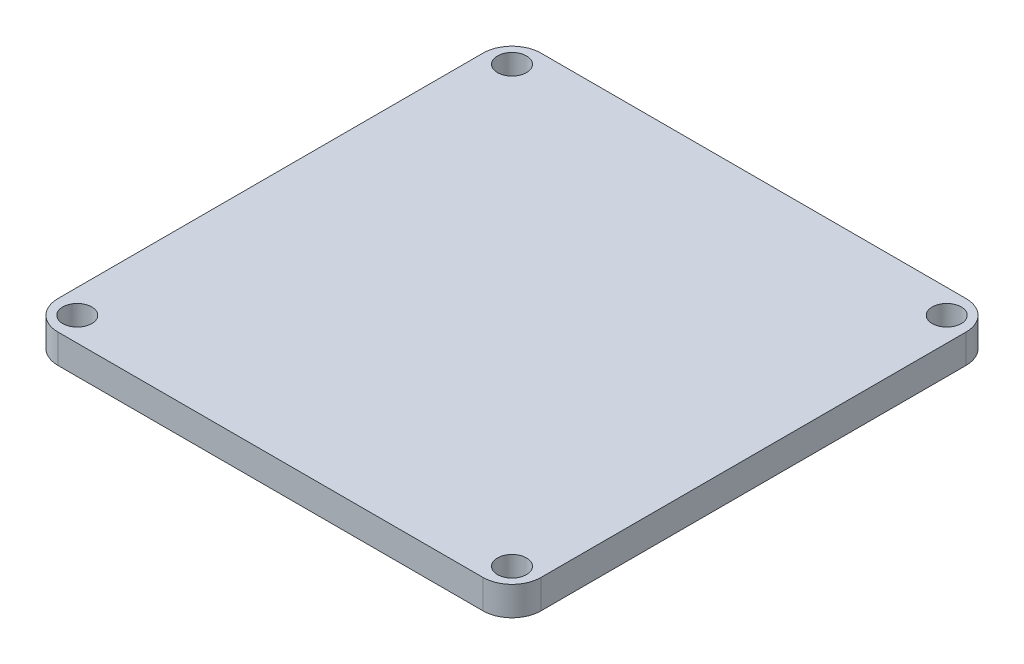
SolidWorks part; units mm, degrees
ref_plane "前基準面" through (0, 0, 0) normal (0, 0, 1) x (1, 0, 0)
ref_plane "上基準面" through (0, 0, 0) normal (0, 1, 0) x (1, 0, 0)
ref_plane "右基準面" through (0, 0, 0) normal (1, 0, 0) x (0, 0, -1)
sketch "草圖1" plane through (0, 0, 0) normal (0, 1, 0) x (1, 0, 0)
  line L1 (-22, 25) -> (22, 25)
  line L2 (-25, 22) -> (-25, -22)
  line L3 (-22, -25) -> (22, -25)
  line L4 (25, 22) -> (25, -22)
  line L5 (-25, 25) -> (25, -25) construction
  line L6 (-25, -25) -> (25, 25) construction
  line L7 (-22.5, -22.5) -> (22.5, -22.5) construction
  line L8 (-22.5, -22.5) -> (-22.5, 22.5) construction
  line L9 (-22.5, 22.5) -> (22.5, 22.5) construction
  line L10 (22.5, -22.5) -> (22.5, 22.5) construction
  line L11 (-22.5, -22.5) -> (22.5, 22.5) construction
  line L12 (-22.5, 22.5) -> (22.5, -22.5) construction
  arc A0 (-25, -22) -> (-22, -25) centre (-22, -22) ccw
  arc A1 (22, -25) -> (25, -22) centre (22, -22) ccw
  arc A2 (22, 25) -> (25, 22) centre (22, 22) cw
  arc A3 (-22, 25) -> (-25, 22) centre (-22, 22) ccw
  circle A4 centre (-22.5, 22.5) radius 1.5
  circle A5 centre (22.5, 22.5) radius 1.5
  circle A6 centre (-22.5, -22.5) radius 1.5
  circle A7 centre (22.5, -22.5) radius 1.5
  point P0 (0, 0)
  point P18 (0, 0)
  point P19 (0, 0)
  dimension "D3" = 3
  dimension "D5" = 3
  dimension "D1" = 50
  dimension "D2" = 50
  dimension "D4" = 45
extrude "填料-伸長1" add sketch "草圖1" along normal blind 3
